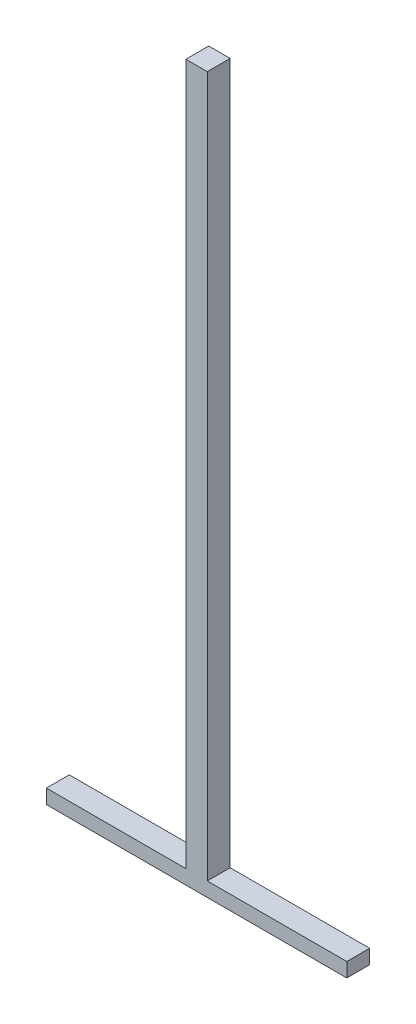
SolidWorks part; units mm, degrees
ref_plane "前视基准面" through (0, 0, 0) normal (0, 0, 1) x (1, 0, 0)
ref_plane "上视基准面" through (0, 0, 0) normal (0, 1, 0) x (1, 0, 0)
ref_plane "右视基准面" through (0, 0, 0) normal (1, 0, 0) x (0, 0, -1)
sketch "草图1" plane through (0, 0, 0) normal (0, 1, 0) x (1, 0, 0)
  line L1 (-49.1204, -19.5828) -> (-7.1204, -19.5828)
  line L2 (-49.1204, -19.5828) -> (-49.1204, -22.7828)
  line L3 (-49.1204, -22.7828) -> (-7.1204, -22.7828)
  line L4 (-7.1204, -19.5828) -> (-7.1204, -22.7828)
  dimension "D1" = 3.2
  dimension "D2" = 42
extrude "凸台-拉伸1" add sketch "草图1" along normal blind 100
sketch "草图4" plane through (0, 0, 19.5828) normal (0, 0, -1) x (-1, 0, 0)
  line L0 (7.1204, 0) -> (49.1204, 0) construction
  line L1 (49.1204, 100) -> (29.6204, 100)
  line L2 (49.1204, 100) -> (49.1204, 2)
  line L3 (49.1204, 2) -> (29.6204, 2)
  line L4 (29.6204, 100) -> (29.6204, 2)
  line L6 (7.1204, 100) -> (26.6204, 100)
  line L7 (7.1204, 100) -> (7.1204, 2)
  line L8 (7.1204, 2) -> (26.6204, 2)
  line L9 (26.6204, 100) -> (26.6204, 2)
  dimension "D1" = 2
  dimension "D2" = 19.5
  dimension "D3" = 19.5
extrude "切除-拉伸2" cut sketch "草图4" against normal through all
